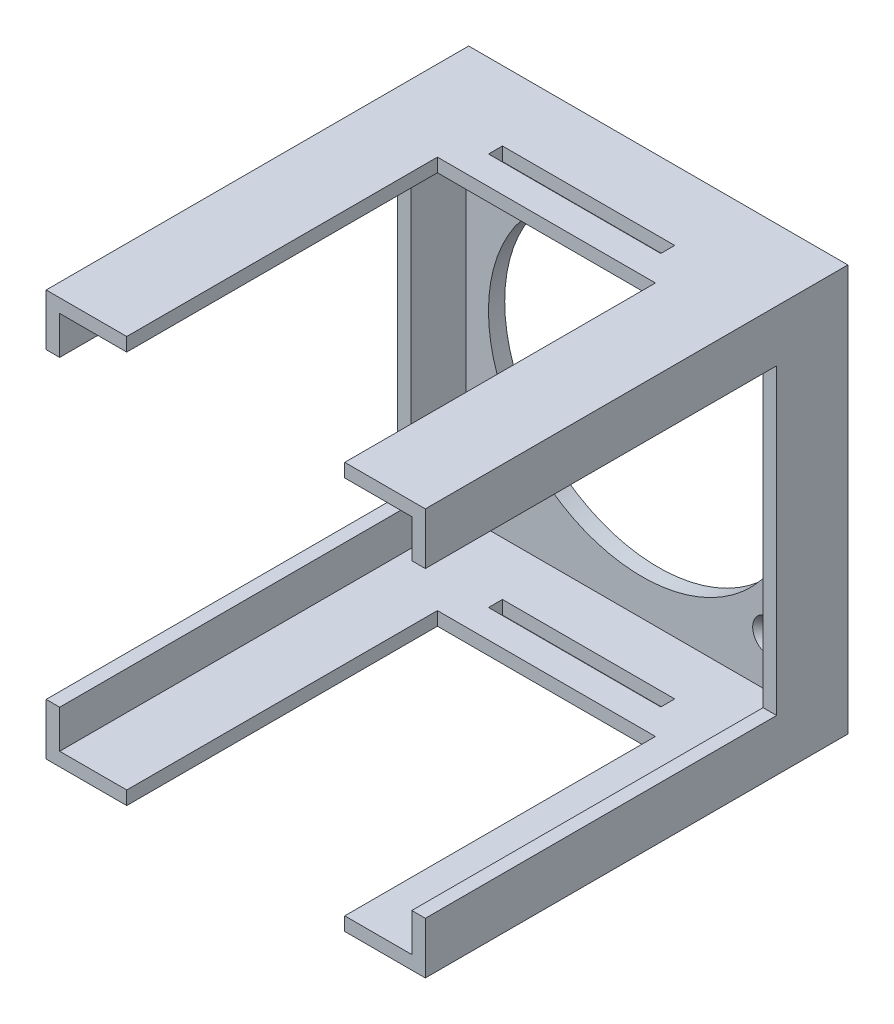
SolidWorks part; units mm, degrees
ref_plane "Plano frontal" through (0, 0, 0) normal (0, 0, 1) x (1, 0, 0)
ref_plane "Plano superior" through (0, 0, 0) normal (0, 1, 0) x (1, 0, 0)
ref_plane "Plano direito" through (0, 0, 0) normal (1, 0, 0) x (0, 0, -1)
sketch "Esboço1" plane through (0, 0, 0) normal (0, 0, 1) x (1, 0, 0)
  line L1 (0, 0) -> (140, 0)
  line L2 (0, 0) -> (0, 150)
  line L3 (0, 150) -> (140, 150)
  line L4 (140, 0) -> (140, 150)
extrude "Ressalto-extrusão1" add sketch "Esboço1" along normal blind 6
sketch "Esboço2" plane through (0, 0, 6) normal (0, 0, 1) x (1, 0, 0)
  line L0 (135, 145) -> (5, 145)
  line L1 (5, 145) -> (5, 5)
  line L2 (5, 5) -> (135, 5)
  line L3 (135, 5) -> (135, 145)
  line L4 (0, 150) -> (0, 0)
  line L5 (0, 0) -> (140, 0)
  line L6 (140, 0) -> (140, 150)
  line L7 (140, 150) -> (0, 150)
  line L8 (0, 150) -> (0, 0)
  line L9 (0, 0) -> (140, 0)
  line L10 (140, 0) -> (140, 150)
  line L11 (140, 150) -> (0, 150)
  dimension "D1" = 0
  dimension "D2" = 5
extrude "Ressalto-extrusão2" add sketch "Esboço2" along normal blind 150 contours L8 L9 L10 L11 | L0 L1 L2 L3
sketch "Esboço3" plane through (0, 0, 0) normal (0, -1, 0) x (1, 0, 0)
  line L0 (70, 156) -> (70, 0) construction
  line L1 (0, 156) -> (140, 156) construction
  line L2 (0, 0) -> (140, 0) construction
  line L4 (110.2437, 285.7049) -> (29.7563, 285.7049)
  line L5 (110.2437, 285.7049) -> (110.2437, 26.2951)
  line L6 (110.2437, 26.2951) -> (29.7563, 26.2951)
  line L7 (29.7563, 285.7049) -> (29.7563, 26.2951)
  line L8 (110.2437, 285.7049) -> (29.7563, 26.2951) construction
  line L9 (110.2437, 26.2951) -> (29.7563, 285.7049) construction
extrude "Corte-extrusão1" cut sketch "Esboço3" against normal blind 150
sketch "Esboço4" plane through (0, 0, 0) normal (-1, 0, 0) x (0, 0, 1)
  line L0 (156, 75) -> (24.2951, 75) construction
  line L1 (156, 150) -> (156, 0) construction
  line L3 (285.7049, 130.9124) -> (26.2951, 130.9124)
  line L4 (285.7049, 130.9124) -> (285.7049, 19.0876)
  line L5 (285.7049, 19.0876) -> (26.2951, 19.0876)
  line L6 (26.2951, 130.9124) -> (26.2951, 19.0876)
  line L7 (285.7049, 130.9124) -> (26.2951, 19.0876) construction
  line L8 (285.7049, 19.0876) -> (26.2951, 130.9124) construction
extrude "Corte-extrusão2" cut sketch "Esboço4" against normal blind 150
sketch "Esboço5" plane through (0, 0, 6) normal (0, 0, 1) x (1, 0, 0)
  line L0 (70, 145) -> (70, 80.7703) construction
  line L1 (29.7563, 145) -> (110.2437, 145) construction
  line L2 (70, 80.7703) -> (0, 75) construction
  line L3 (0, 130.9124) -> (0, 19.0876) construction
  line L4 (0, 75) -> (52.689, 75) construction
  circle A0 centre (22.8426, 22.6692) radius 3
  circle A1 centre (117.1574, 22.6692) radius 3
  circle A2 centre (117.1574, 127.3308) radius 3
  circle A3 centre (22.8426, 127.3308) radius 3
hole_wizard "Escareado para parafuso com cabeça escareada elevada de M61" positions "3DSketch1" profile "Esboço6" countersink size "M6" standard "DIN" end condition through all
sketch3d "3DSketch1"
  point P0 (22.8426, 127.3308, 6)
  point P3 (117.1574, 127.3308, 6)
  point P6 (22.8426, 22.6692, 6)
  point P9 (117.1574, 22.6692, 6)
sketch "Esboço6" plane through (22.8426, 127.3308, 6) normal (1, 0, 0) x (0, -1, 0)
  line L0 (0, 0) -> (0, 6)
  line L1 (0, 6) -> (3.5, 6)
  line L2 (3.5, 6) -> (3.5, 2.8)
  line L3 (3.5, 2.8) -> (6.3, 0)
  line L5 (6.3, 0) -> (0, 0)
  line L6 (-3.5, 2.8) -> (-6.3, 0) construction
  line L11 (0, -6.35) -> (0, 107.95) construction
  dimension "Thru Hole Dia." = 7
  dimension "Thru Hole Depth" = 6
  dimension "Near C'Sink Dia." = 12.6
  dimension "Near C'Sink Angle" = 90
sketch "Esboço11" plane through (0, 0, 26.2951) normal (0, 0, 1) x (1, 0, 0)
  line L1 (29.7563, 150) -> (110.2437, 150)
  line L2 (29.7563, 150) -> (29.7563, 145)
  line L3 (29.7563, 145) -> (110.2437, 145)
  line L4 (110.2437, 150) -> (110.2437, 145)
  line L5 (29.7563, 0) -> (110.2437, 0)
  line L6 (29.7563, 0) -> (29.7563, 5)
  line L7 (29.7563, 5) -> (110.2437, 5)
  line L8 (110.2437, 0) -> (110.2437, 5)
extrude "Ressalto-extrusão5" add sketch "Esboço11" along normal blind 15
sketch "Esboço12" plane through (0, 0, 0) normal (0, -1, 0) x (1, 0, 0)
  line L0 (70, 41.2951) -> (70, 25.7291) construction
  line L1 (38.1949, 25.7291) -> (101.8051, 25.7291)
  line L2 (38.1949, 25.7291) -> (38.1949, 30.8646)
  line L3 (38.1949, 30.8646) -> (101.8051, 30.8646)
  line L4 (101.8051, 25.7291) -> (101.8051, 30.8646)
  line L5 (29.7563, 41.2951) -> (110.2437, 41.2951) construction
extrude "Corte-extrusão3" cut sketch "Esboço12" against normal blind 219
sketch "Esboço13" plane through (0, 0, 6) normal (0, 0, 1) x (1, 0, 0)
  circle A0 centre (70, 75) radius 56.6934
extrude "Corte-extrusão4" cut sketch "Esboço13" against normal blind 10
